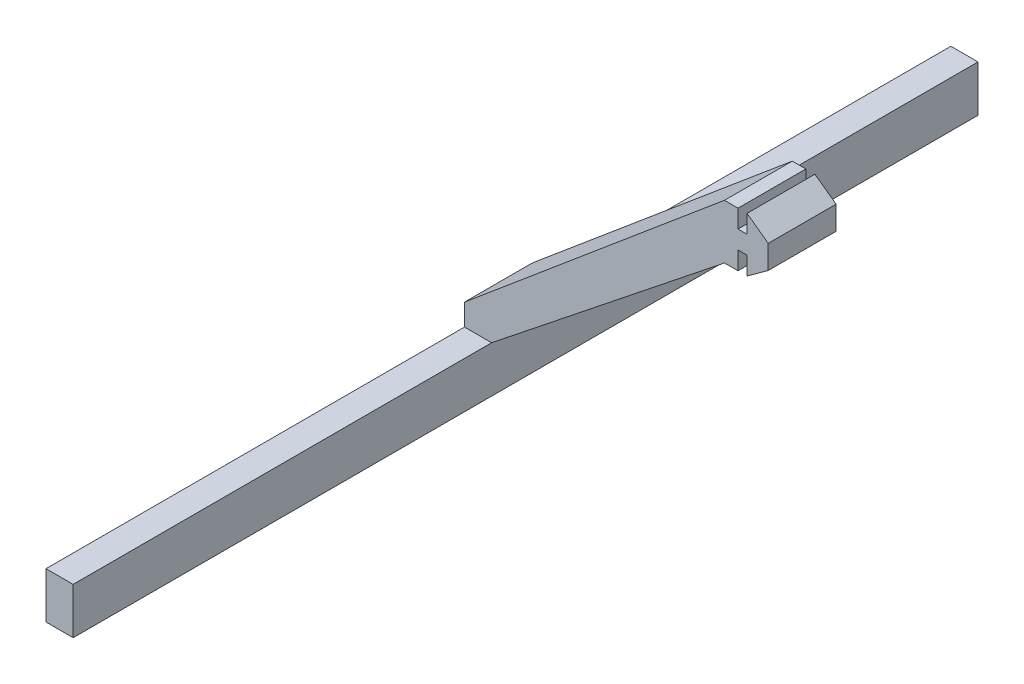
SolidWorks part; units mm, degrees
ref_plane "Plan de face" through (0, 0, 0) normal (0, 0, 1) x (1, 0, 0)
ref_plane "Plan de dessus" through (0, 0, 0) normal (0, 1, 0) x (1, 0, 0)
ref_plane "Plan de droite" through (0, 0, 0) normal (1, 0, 0) x (0, 0, -1)
sketch "Esquisse1" plane through (0, 0, 0) normal (0, 0, 1) x (1, 0, 0)
  line L0 (0, 4.7594) -> (4.68, 1.3594)
  line L1 (4.68, 1.3594) -> (4.68, -3.8406)
  line L2 (4.68, -3.8406) -> (0, -7.2406)
  line L3 (0, 4.7594) -> (0, -7.2406)
  point P3 (0, 0)
  dimension "D1" = 5.2
  dimension "D2" = 12
  dimension "D3" = 3.4
  dimension "D4" = 3.4
  dimension "D5" = 4.68
extrude "Boss.-Extru.1" add sketch "Esquisse1" along normal blind 15
sketch "Esquisse3" plane through (0, 0, 0) normal (-1, 0, 0) x (0, 0, 1)
  line L0 (0, 4.7594) -> (0, -7.2406) construction
  line L1 (0, 0.7594) -> (15, 0.7594)
  line L2 (0, 0.7594) -> (0, -3.2406)
  line L3 (0, -3.2406) -> (15, -3.2406)
  line L4 (15, 0.7594) -> (15, -3.2406)
  line L5 (15, 4.7594) -> (15, -7.2406) construction
  line L6 (15, 4.7594) -> (0, 4.7594) construction
  line L7 (15, -7.2406) -> (0, -7.2406) construction
  dimension "D1" = 0
  dimension "D2" = 0
  dimension "D3" = 4
  dimension "D4" = 4
  dimension "D5" = 4
extrude "Boss.-Extru.2" add sketch "Esquisse3" along normal blind 2
sketch "Esquisse4" plane through (-2, 0, 0) normal (-1, 0, 0) x (0, 0, 1)
  line L1 (0, 4.7594) -> (15, 4.7594)
  line L2 (0, 4.7594) -> (0, -7.2406)
  line L3 (0, -7.2406) -> (15, -7.2406)
  line L4 (15, 4.7594) -> (15, -7.2406)
extrude "Boss.-Extru.3" add sketch "Esquisse4" along normal blind 3
sketch "Esquisse5" plane through (0, 0, 0) normal (0, 0, -1) x (-1, 0, 0)
  line L0 (5, 4.7594) -> (62.4533, -43.4497)
  line L1 (62.4533, -43.4497) -> (50.4533, -43.4497)
  line L2 (50.4533, -43.4497) -> (5, -7.2406)
  line L3 (5, -7.2406) -> (5, 4.7594)
  dimension "D1" = 50
  dimension "D2" = 75
  dimension "D3" = 12
extrude "Boss.-Extru.4" add sketch "Esquisse5" against normal blind 15
sketch "Esquisse6" plane through (0, -43.4497, 0) normal (0, -1, 0) x (-1, 0, 0)
  line L0 (50.4533, -15) -> (62.4533, -15) construction
  line L1 (56.4533, -15) -> (62.4533, -15)
  line L2 (56.4533, -15) -> (56.4533, 0)
  line L3 (56.4533, 0) -> (62.4533, 0)
  line L4 (62.4533, -15) -> (62.4533, 0)
  dimension "D1" = 6
extrude "Boss.-Extru.5" add sketch "Esquisse6" along normal blind 15
sketch "Esquisse7" plane through (0, 0, 0) normal (0, 0, -1) x (-1, 0, 0)
  line L0 (50.4533, -43.4497) -> (56.4533, -48.2294)
  line L1 (56.4533, -58.4497) -> (56.4533, -43.4497) construction
  line L2 (56.4533, -48.2294) -> (56.4533, -43.4497)
  line L3 (56.4533, -43.4497) -> (50.4533, -43.4497)
extrude "Boss.-Extru.6" add sketch "Esquisse7" against normal blind 15
sketch "Esquisse8" plane through (-62.4533, 0, 0) normal (-1, 0, 0) x (0, 0, 1)
  line L0 (15, -58.4497) -> (0, -58.4497) construction
  line L1 (107.5, -48.2297) -> (-92.5, -48.2297)
  line L2 (107.5, -48.2297) -> (107.5, -58.4497)
  line L3 (107.5, -58.4497) -> (-92.5, -58.4497)
  line L4 (-92.5, -48.2297) -> (-92.5, -58.4497)
  line L5 (15, -58.4497) -> (15, -43.4497) construction
  dimension "D1" = 10.22
  dimension "D2" = 0
  dimension "D3" = 200
  dimension "D4" = 92.5
extrude "Boss.-Extru.7" add sketch "Esquisse8" against normal blind 6
